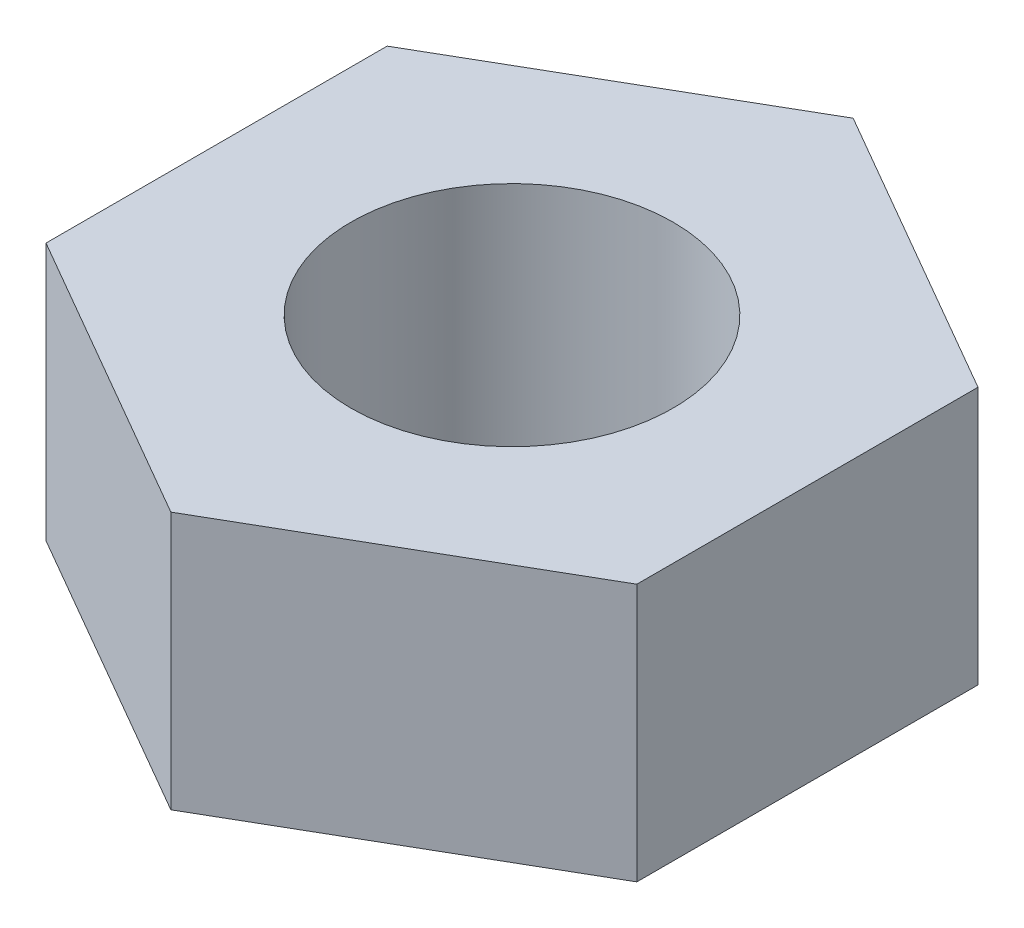
SolidWorks part; units mm, degrees
material "铸造不锈钢"
ref_plane "前视基准面" through (0, 0, 0) normal (0, 0, 1) x (1, 0, 0)
ref_plane "上视基准面" through (0, 0, 0) normal (0, 1, 0) x (1, 0, 0)
ref_plane "右视基准面" through (0, 0, 0) normal (1, 0, 0) x (0, 0, -1)
other "Configuration Table"
sketch "草图1" plane through (0, 0, 0) normal (0, 1, 0) x (1, 0, 0)
  line L0 (0, 0) -> (0, 4.1316) construction
  line L1 (2.75, 1.5877) -> (0, 3.1754)
  line L2 (0, 3.1754) -> (-2.75, 1.5877)
  line L3 (-2.75, 1.5877) -> (-2.75, -1.5877)
  line L4 (-2.75, -1.5877) -> (0, -3.1754)
  line L5 (0, -3.1754) -> (2.75, -1.5877)
  line L6 (2.75, -1.5877) -> (2.75, 1.5877)
  circle A0 centre (0, 0) radius 1.5
  circle A1 centre (0, 0) radius 2.75 construction
  dimension "D1" = 3
  dimension "D2" = 5.5
extrude "凸台-拉伸1" add sketch "草图1" along normal blind 2.4
